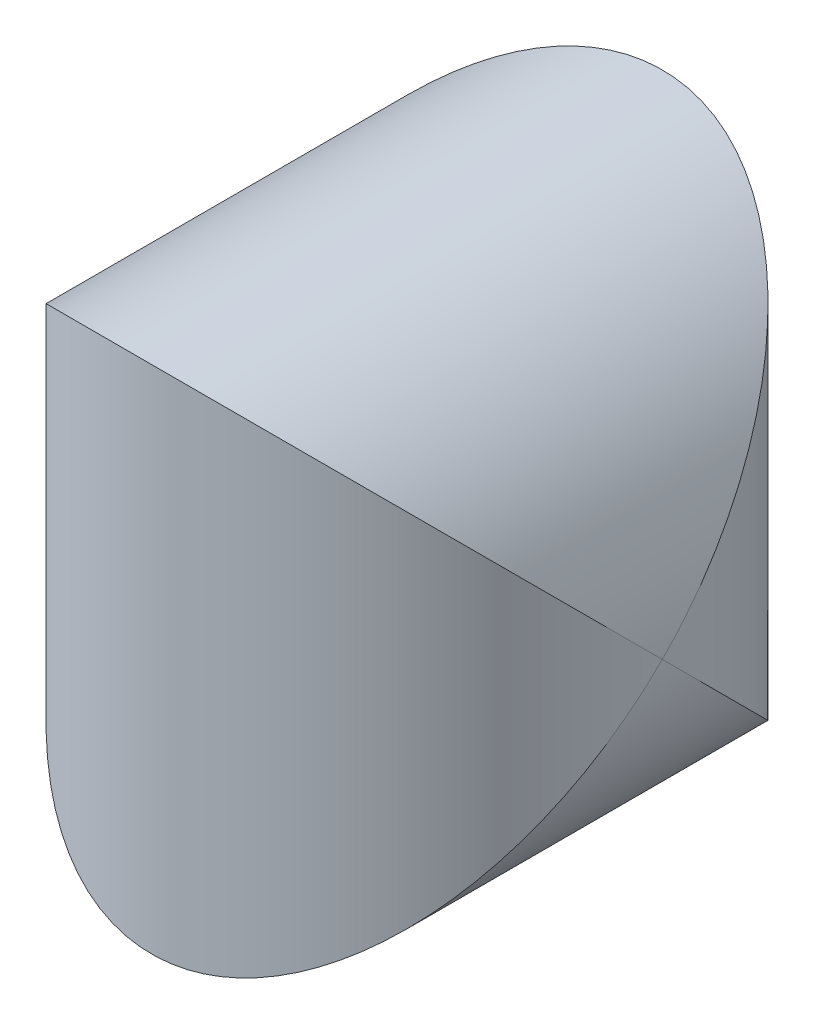
SolidWorks part; units mm, degrees
ref_plane "前视基准面" through (0, 0, 0) normal (0, 0, 1) x (1, 0, 0)
ref_plane "上视基准面" through (0, 0, 0) normal (0, 1, 0) x (1, 0, 0)
ref_plane "右视基准面" through (0, 0, 0) normal (1, 0, 0) x (0, 0, -1)
other "Configuration Table"
sketch "草图1" plane through (0, 0, 0) normal (0, 1, 0) x (1, 0, 0)
  circle A0 centre (0, 0) radius 25
  dimension "D1" = 50
extrude "凸台-拉伸1" add sketch "草图1" along normal mid plane 50
sketch "草图2" plane through (0, 0, 0) normal (0, 0, 1) x (1, 0, 0)
  circle A0 centre (0, 0) radius 25
  dimension "D1" = 50
extrude "切除-拉伸1" cut sketch "草图2" against normal mid plane 80 flip side to cut
